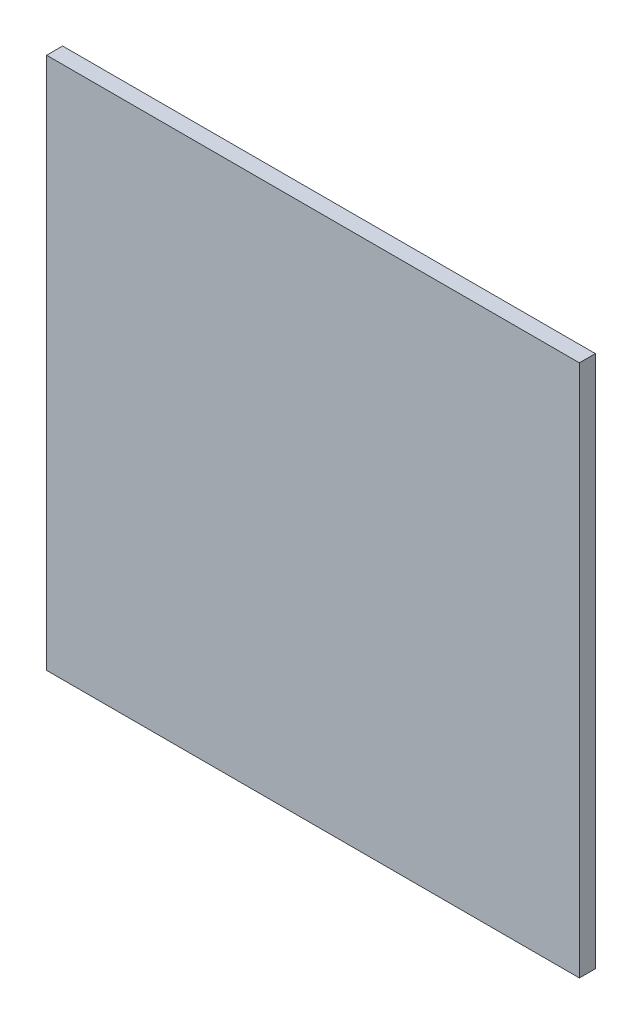
SolidWorks part; units mm, degrees
material "ABS"
ref_plane "Front Plane" through (0, 0, 0) normal (0, 0, 1) x (1, 0, 0)
ref_plane "Top Plane" through (0, 0, 0) normal (0, 1, 0) x (1, 0, 0)
ref_plane "Right Plane" through (0, 0, 0) normal (1, 0, 0) x (0, 0, -1)
sketch "Sketch1" plane through (0, 0, 0) normal (0, 0, 1) x (1, 0, 0)
  line L0 (74.1496, -324.9742) -> (571.4829, -324.9742) construction
  line L1 (-50, 50) -> (50, 50)
  line L2 (-50, 50) -> (-50, -50)
  line L3 (-50, -50) -> (50, -50)
  line L4 (50, 50) -> (50, -50)
  line L5 (-50, 50) -> (50, -50) construction
  line L6 (-50, -50) -> (50, 50) construction
  point P0 (0, 0)
  dimension "D1" = 100
extrude "Boss-Extrude1" add sketch "Sketch1" along normal blind 3
